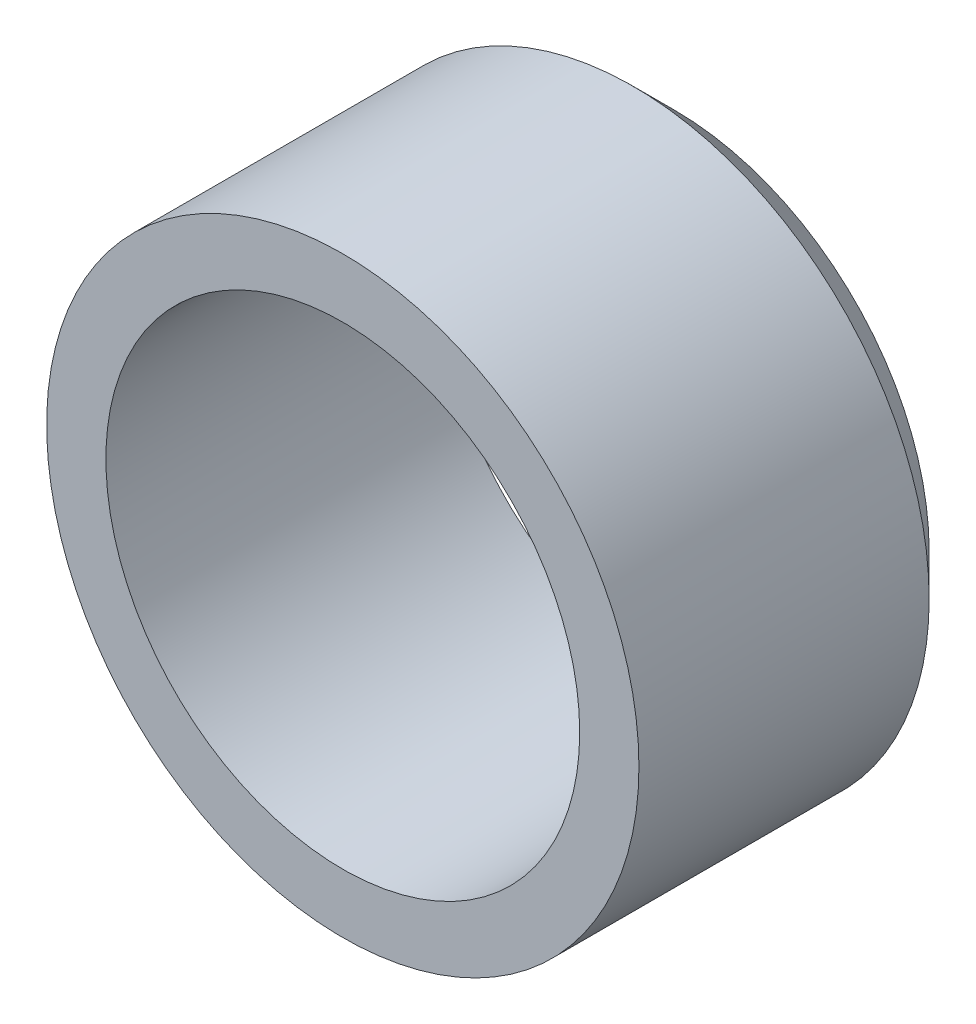
SolidWorks part; units mm, degrees
ref_plane "Front Plane" through (0, 0, 0) normal (0, 0, 1) x (1, 0, 0)
ref_plane "Top Plane" through (0, 0, 0) normal (0, 1, 0) x (1, 0, 0)
ref_plane "Right Plane" through (0, 0, 0) normal (1, 0, 0) x (0, 0, -1)
sketch "Sketch1" plane through (0, 0, 0) normal (1, 0, 0) x (0, 0, -1)
  line L0 (-20.7004, 0) -> (18.1553, 0) construction
  line L1 (2.75, 0) -> (-2.75, 0) construction
  line L2 (0, 55) -> (0, -55) construction
  line L3 (0, 2.5) -> (2.8, 2.5)
  line L4 (2.8, 2.5) -> (2.8, 1.5)
  line L5 (2.8, 1.5) -> (4, 1.5)
  line L6 (4, 1.5) -> (4, 0.5)
  line L7 (4, 0.5) -> (2, 0.5)
  line L8 (2, 0.5) -> (2, 2)
  line L9 (2, 2) -> (0, 2)
  line L10 (0, 2) -> (0, 2.5)
  dimension "D1" = 5
  dimension "D2" = 4
  dimension "D3" = 2
  dimension "D4" = 0.8
  dimension "D5" = 2
  dimension "D6" = 1
  dimension "D7" = 1
revolve "Revolve1" add sketch "Sketch1" angle 360 about L0
chamfer "Fase1" distance 0.35 angle 45 1 edges at (2.5, 0, -2.8)
sketch "Skizze1" plane through (0, 0, -2) normal (0, 0, 1) x (1, 0, 0)
  circle A1 centre (0, 0) radius 2 construction
  circle A2 centre (0, 0) radius 2
extrude "Schnitt-Linear austragen1" cut sketch "Skizze1" against normal through all
